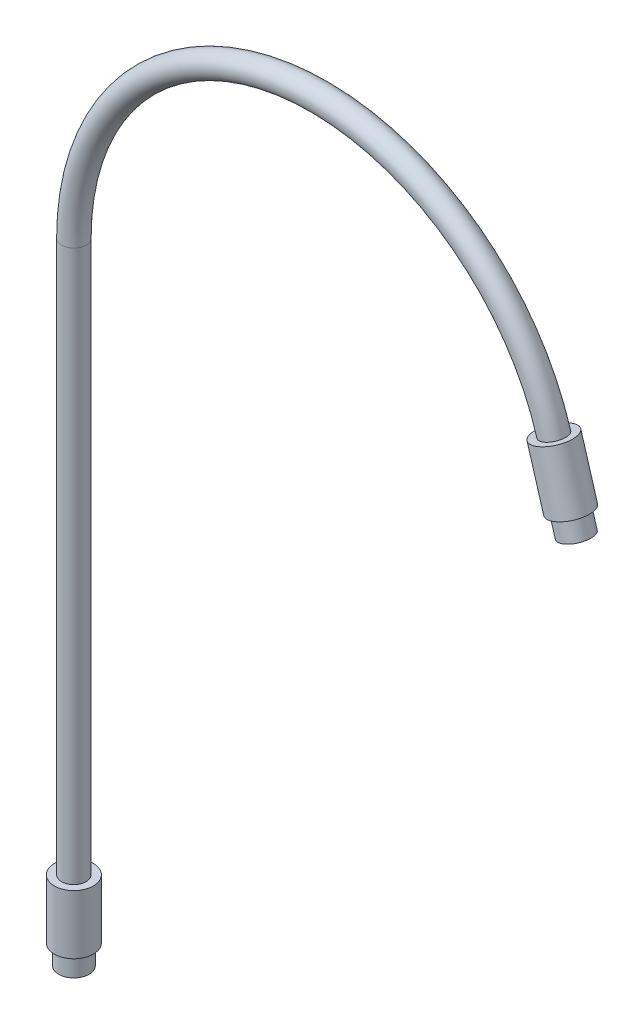
SolidWorks part; units mm, degrees
ref_plane "Front Plane" through (0, 0, 0) normal (0, 0, 1) x (1, 0, 0)
ref_plane "Top Plane" through (0, 0, 0) normal (0, 1, 0) x (1, 0, 0)
ref_plane "Right Plane" through (0, 0, 0) normal (1, 0, 0) x (0, 0, -1)
sketch "Sketch9" plane through (0, 0, 0) normal (0, 0, 1) x (1, 0, 0)
  line L0 (-183.3991, 40) -> (-183.3991, 180)
  arc A0 (-183.3991, 180) -> (-61.493, 197.7129) centre (-121.1592, 180) cw
  dimension "D1" = 140
sweep "Sweep3" add path "Sketch9" circular profile diameter 6.2 parameters "D3"=6.2
sketch "Sketch17" plane through (0, 40, 0) normal (0, -1, 0) x (1, 0, 0)
  circle A0 centre (-183.3991, 0) radius 4.95
  circle A1 centre (-183.3991, 0) radius 3.1 construction
  dimension "D2" = 9.9
  dimension "D1" = 0
extrude "Boss-Extrude1" add sketch "Sketch17" along normal blind 15
sketch "Sketch18" plane through (0, 25, 0) normal (0, -1, 0) x (1, 0, 0)
  circle A0 centre (-183.3991, 0) radius 3.85
  dimension "D1" = 7.7
extrude "Boss-Extrude2" add sketch "Sketch18" along normal blind 5
sketch "Sketch19" plane through (-58.9208, 198.4764, 0) normal (0.2846, -0.9586, 0) x (0.9586, 0.2846, 0)
  circle A0 centre (-2.6831, 0) radius 4.95
  dimension "D1" = 9.9
extrude "Boss-Extrude3" add sketch "Sketch19" along normal blind 15
sketch "Sketch20" plane through (-54.652, 184.0967, 0) normal (0.2846, -0.9586, 0) x (0.9586, 0.2846, 0)
  circle A0 centre (-2.6831, 0) radius 3.85
  dimension "D1" = 7.7
extrude "Boss-Extrude4" add sketch "Sketch20" along normal blind 5
